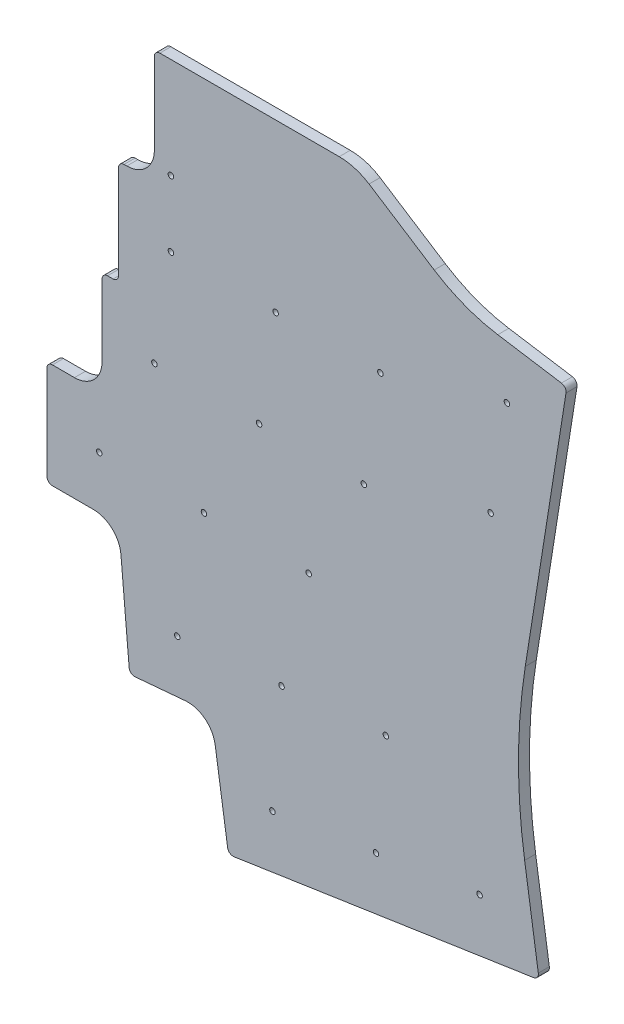
SolidWorks part; units mm, degrees
ref_plane "Front Plane" through (0, 0, 0) normal (1, 0, 0) x (0, 1, 0)
ref_plane "Top Plane" through (0, 0, 0) normal (0, 0, 1) x (0, 1, 0)
ref_plane "Right Plane" through (0, 0, 0) normal (0, 1, 0) x (-1, 0, 0)
sketch "Sketch1" plane through (0, 0, 0) normal (0, 0, 1) x (0, 1, 0)
  line L8 (-59.8119, -1.1446) -> (-54.6791, -59.8133) construction
  line L13 (-12, -58) -> (4.1691, -60.5609) construction
  line L39 (-9.5, 0) -> (0, 0) construction
  line L52 (-54.6791, -59.8133) -> (-54.6791, -52.5468) construction
  line L61 (-78.6592, -18.4238) -> (-72.5284, -59.1312) construction
  line L66 (-83.2969, -48.3987) -> (-65.3987, -45.7031) construction
  line L67 (-72.5284, -59.1312) -> (-72.5284, -50.1661) construction
  line L76 (-12, -58) -> (-14.5099, -73.8469) construction
  line L77 (-9.05, -47.05) -> (9.05, -47.05) construction
  line L78 (-9.05, -47.05) -> (-9.05, -28.95) construction
  line L79 (-9.05, -28.95) -> (9.05, -28.95) construction
  line L80 (-14.5099, -73.8469) -> (-14.5099, -58.3106) construction
  line L81 (-89.4681, -10.4445) -> (-68.8068, -7.3328)
  line L82 (9.05, -47.05) -> (9.05, -28.95) construction
  line L83 (-22.3543, -65.5228) -> (-4.4772, -68.3543) construction
  line L84 (-22.3543, -65.5228) -> (-19.5228, -47.6457) construction
  line L85 (-19.5228, -47.6457) -> (-1.6457, -50.4772) construction
  line L95 (11, 1) -> (28.24, 1) construction
  line L96 (12, 0) -> (27.24, 0) construction
  line L97 (12, 0) -> (12, -30.48) construction
  line L98 (12, -30.48) -> (27.24, -30.48) construction
  line L99 (27.24, 0) -> (27.24, -30.48) construction
  line L100 (28.24, 1) -> (28.24, -31.48) construction
  line L101 (11, -31.48) -> (28.24, -31.48) construction
  line L102 (11, 1) -> (11, -31.48) construction
  line L103 (19.62, -0.9837) -> (19.62, 0) construction
  line L104 (16.12, 0) -> (23.12, 0) construction
  line L105 (16.12, 0) -> (16.12, -0.9837) construction
  line L106 (16.12, -0.9837) -> (23.12, -0.9837) construction
  line L107 (23.12, 0) -> (23.12, -0.9837) construction
  line L115 (-73, -56) -> (-71.8296, -63.7713) construction
  line L120 (-4.4772, -68.3543) -> (-1.6457, -50.4772) construction
  line L121 (29.031, 0) -> (27.24, 0) construction
  line L122 (27.24, 0) -> (27.24, 1.791) construction
  line L123 (-65.3987, -45.7031) -> (-62.7031, -63.6013) construction
  line L128 (-62.7031, -63.6013) -> (-80.6013, -66.2969) construction
  line L129 (-80.6013, -66.2969) -> (-83.2969, -48.3987) construction
  line L130 (-64.7268, -48.8043) -> (-46.6957, -47.2268) construction
  line L131 (-46.6957, -47.2268) -> (-48.2732, -29.1957) construction
  line L132 (-48.2732, -29.1957) -> (-66.3043, -30.7732) construction
  line L133 (-66.3043, -30.7732) -> (-64.7268, -48.8043) construction
  line L134 (-47.05, -34.05) -> (-28.95, -34.05) construction
  line L135 (-47.05, -34.05) -> (-47.05, -15.95) construction
  line L136 (-47.05, -15.95) -> (-28.95, -15.95) construction
  line L137 (-28.95, -34.05) -> (-28.95, -15.95) construction
  line L138 (-68.8068, -7.3328) -> (-70.1037, 7.4913)
  line L139 (-70.1037, 7.4913) -> (-47.5, 9.4688)
  line L140 (-47.5, 9.4688) -> (-47.5, 22.5)
  line L141 (-47.5, 22.5) -> (-28.5, 22.5)
  line L142 (-28.5, 22.5) -> (-28.5, 12.5)
  line L143 (-28.5, 12.5) -> (-9.5, 12.5)
  line L144 (-9.5, 12.5) -> (-9.5, 9.5)
  line L145 (-9.5, 9.5) -> (9.5, 9.5)
  line L146 (9.5, 9.5) -> (9.5, 3)
  line L147 (9.5, 3) -> (30.24, 3)
  line L148 (30.24, 3) -> (30.24, -33.48)
  line L149 (30.24, -33.48) -> (17.6352, -53.0753)
  line L150 (-89.4681, -10.4445) -> (-80.9793, -66.8089)
  line L151 (-78.6592, -18.4238) -> (-88.0533, -19.8386) construction
  line L152 (-78.6592, -18.4238) -> (-80.074, -9.0297) construction
  line L153 (-59.8119, -1.1446) -> (-69.2758, -1.9726) construction
  line L154 (-59.8119, -1.1446) -> (-60.6399, 8.3192) construction
  line L155 (-47.5, 13) -> (-38, 13) construction
  line L156 (-38, 13) -> (-28.5, 13) construction
  line L157 (-38, 13) -> (-38, 22.5) construction
  line L158 (-19, 3) -> (-19, 12.5) construction
  line L159 (-19, 3) -> (-9.5, 3) construction
  line L160 (0, 0) -> (0, 9.5) construction
  line L161 (0, 0) -> (9.5, 0) construction
  line L162 (14.2889, -71.3266) -> (-3.5882, -68.4951) construction
  line L163 (-3.5882, -68.4951) -> (-0.7568, -50.6179) construction
  line L164 (-0.7568, -50.6179) -> (17.1204, -53.4494) construction
  line L165 (17.1204, -53.4494) -> (14.2889, -71.3266) construction
  line L166 (-48.2415, -61.8783) -> (14.663, -71.8414)
  line L167 (14.663, -71.8414) -> (17.6352, -53.0753)
  line L168 (-80.9793, -66.8089) -> (-48.2415, -61.8783)
  line L169 (-73, -56) -> (-71.5852, -65.3941) construction
  line L170 (6.7661, -60.9723) -> (16.1491, -62.4584) construction
  line L171 (6.7661, -60.9723) -> (5.28, -70.3553) construction
  circle A6 centre (-56.5, -39) radius 0.5
  circle A7 centre (-73, -56) radius 0.5
  circle A17 centre (0, 0) radius 0.5
  circle A24 centre (-38, 13) radius 0.5
  circle A27 centre (-19, 3) radius 0.5
  circle A30 centre (12, 0) radius 0.5
  circle A31 centre (-12, -58) radius 0.5
  circle A33 centre (0, -19) radius 0.5
  circle A34 centre (-19, -16) radius 0.5
  circle A35 centre (-38, -6) radius 0.5
  circle A36 centre (0, -38) radius 0.5
  circle A37 centre (-19, -35) radius 0.5
  circle A38 centre (-38, -25) radius 0.5
  circle A39 centre (-58.156, -20.0723) radius 0.5
  circle A40 centre (-59.8119, -1.1446) radius 0.5
  circle A41 centre (-75.8296, -37.2119) radius 0.5
  circle A42 centre (-78.6592, -18.4238) radius 0.5
  circle A43 centre (6.7661, -60.9723) radius 0.5
  circle A44 centre (-12, -58) radius 12.7986 construction
  circle A45 centre (0, -38) radius 12.7986 construction
  circle A46 centre (-19, -35) radius 12.7986 construction
  circle A47 centre (-73, -56) radius 12.7986 construction
  circle A48 centre (-56.5, -39) radius 12.7986 construction
  circle A49 centre (-38, -25) radius 12.7986 construction
  circle A50 centre (6.7661, -60.9723) radius 12.7986 construction
  point P20 (24.39, -0.9837)
  point P28 (31.571, 0)
  point P135 (19.62, 1)
  dimension "D25" = 12
  dimension "D26" = 18.1
  dimension "D29" = 90
  dimension "D33" = 9.5
  dimension "D30" = 8.9651
  dimension "D31" = 9.5
  dimension "D40" = 12
  dimension "D46" = 2
  dimension "D43" = 1
  dimension "D63" = 17
  dimension "D9" = 39
  dimension "D8" = 3
  dimension "D12" = 10
  dimension "D13" = 3
  dimension "D15" = 18.5
  dimension "D17" = 3
  dimension "D20" = 3
  dimension "D22" = 1
  dimension "D5" = 2
  dimension "D7" = 19
  dimension "D27" = 9
  dimension "D28" = 9.5
  dimension "D10" = 19
  dimension "D11" = 19
  dimension "D14" = 19
  dimension "D16" = 16.5
  dimension "D18" = 19
  dimension "D19" = 5
  dimension "D21" = 19
  dimension "D23" = 20
  dimension "D24" = 8.565
  dimension "D37" = 15.24
  dimension "D38" = 30.48
  dimension "D42" = 7
  dimension "D44" = 2
  dimension "D45" = 2
  dimension "D39" = 1
extrude "Boss-Extrude1" add sketch "Sketch1" along normal blind 2
fillet "Fillet1" radius 30 1 edges at (53.0753, 17.6352, 1)
fillet "Fillet5" radius 100 1 edges at (61.8783, -48.2415, 1)
fillet "Fillet2" radius 10 1 edges at (33.48, 30.24, 1)
fillet "Fillet3" radius 1 10 edges at (-3, 30.24, 1) (-9.5, 9.5, 1) (-12.5, -9.5, 1) (-22.5, -28.5, 1) (-22.5, -47.5, 1) (-7.4913, -70.1037, 1) (10.4445, -89.4681, 1) (66.8089, -80.9793, 1) (71.8414, 14.663, 1) (-9.5, -9.5, 1)
fillet "Fillet4" radius 5 4 edges at (7.3328, -68.8068, 1) (-12.5, -28.5, 1) (-9.4688, -47.5, 1) (-3, 9.5, 1)
